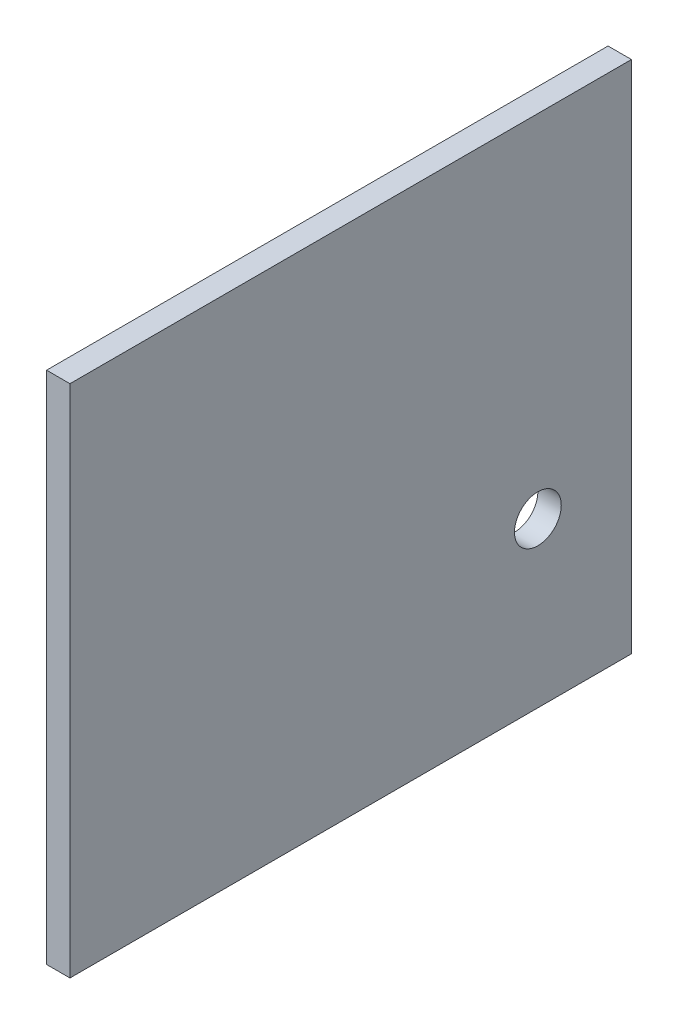
SolidWorks part; units mm, degrees
ref_plane "Front Plane" through (0, 0, 0) normal (0, 0, 1) x (1, 0, 0)
ref_plane "Top Plane" through (0, 0, 0) normal (0, 1, 0) x (1, 0, 0)
ref_plane "Right Plane" through (0, 0, 0) normal (1, 0, 0) x (0, 0, -1)
sketch "Sketch1" plane through (0, 0, 0) normal (1, 0, 0) x (0, 0, -1)
  line L1 (-60, 55) -> (60, 55)
  line L2 (-60, 55) -> (-60, -55)
  line L3 (-60, -55) -> (60, -55)
  line L4 (60, 55) -> (60, -55)
  line L5 (-60, 55) -> (60, -55) construction
  line L6 (-60, -55) -> (60, 55) construction
  point P0 (0, 0)
  dimension "D1" = 120
  dimension "D2" = 110
extrude "Boss-Extrude1" add sketch "Sketch1" along normal blind 5
sketch "Sketch2" plane through (5, 0, 0) normal (1, 0, 0) x (0, 0, -1)
  line L0 (60, -55) -> (60, 55) construction
  line L1 (-60, -55) -> (60, -55) construction
  circle A0 centre (40, -20) radius 5
  dimension "D1" = 10
  dimension "D2" = 20
  dimension "D3" = 35
extrude "Cut-Extrude1" cut sketch "Sketch2" against normal through all
